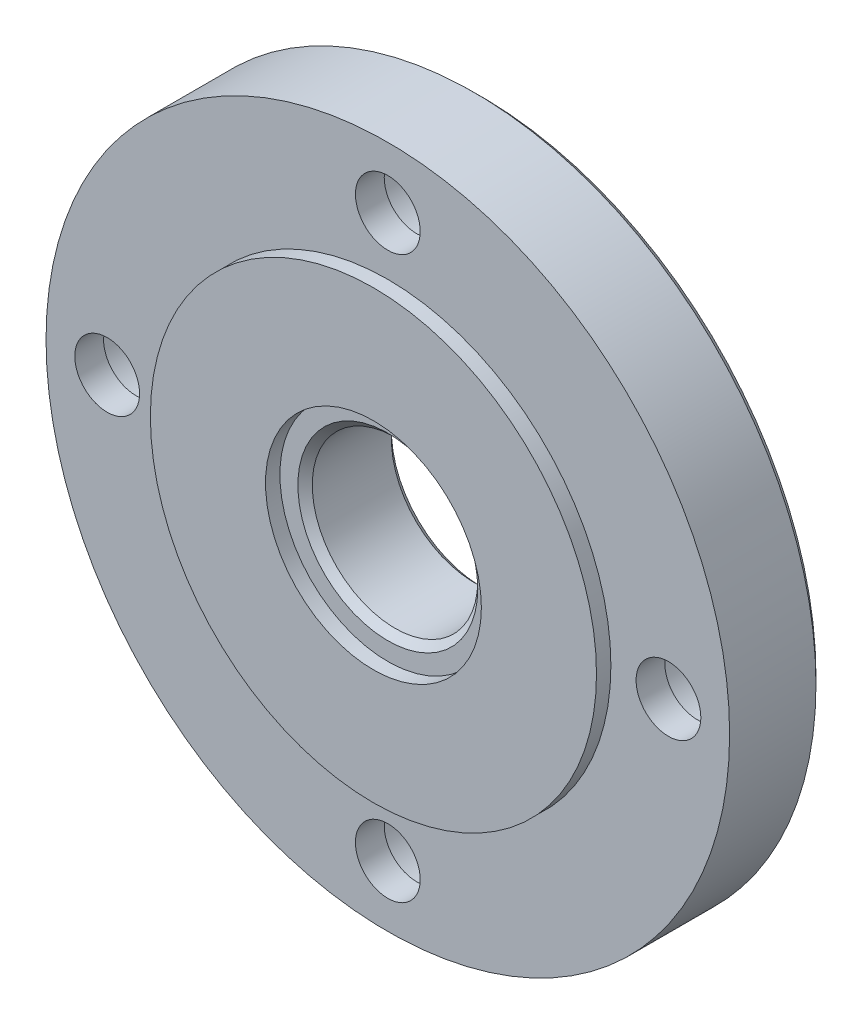
SolidWorks part; units mm, degrees
ref_plane "前视基准面" through (0, 0, 0) normal (0, 0, 1) x (1, 0, 0)
ref_plane "上视基准面" through (0, 0, 0) normal (0, 1, 0) x (1, 0, 0)
ref_plane "右视基准面" through (0, 0, 0) normal (1, 0, 0) x (0, 0, -1)
sketch "草图1" plane through (0, 0, 0) normal (0, 0, 1) x (1, 0, 0)
  circle A0 centre (0, 0) radius 47.5
  dimension "D1" = 95
extrude "凸台-拉伸1" add sketch "草图1" along normal blind 13
sketch "草图2" plane through (0, 0, 13) normal (0, 0, 1) x (1, 0, 0)
  circle A0 centre (0, 0) radius 31
  dimension "D1" = 62
extrude "凸台-拉伸2" add sketch "草图2" along normal blind 2
sketch "草图3" plane through (0, 0, 15) normal (0, 0, 1) x (1, 0, 0)
  circle A0 centre (0, 0) radius 15
  dimension "D1" = 30
extrude "切除-拉伸2" cut sketch "草图3" against normal blind 2
sketch "草图6" plane through (0, 0, 13) normal (0, 0, 1) x (1, 0, 0)
  circle A0 centre (0, 0) radius 11.5
  dimension "D1" = 23
extrude "切除-拉伸3" cut sketch "草图6" against normal through all
chamfer "倒角1" distance 1 angle 45 2 edges at (11.5, 0, 13) (11.5, 0, 0)
sketch "草图7" plane through (0, 0, 0) normal (0, 0, -1) x (-1, 0, 0)
  circle A0 centre (0, 0) radius 39 construction
  circle A1 centre (0, 39) radius 7
  dimension "D1" = 78
  dimension "D2" = 14
extrude "切除-拉伸4" cut sketch "草图7" against normal blind 9
sketch "草图8" plane through (0, 0, 9) normal (0, 0, -1) x (-1, 0, 0)
  circle A0 centre (0, 39) radius 4.5
  circle A1 centre (0, 39) radius 7 construction
  dimension "D1" = 9
extrude "切除-拉伸5" cut sketch "草图8" against normal through all
pattern_circular "阵列(圆周)1" count 4 over 360 about axis through (0, 0, 0) along (0, 0, 1) of "切除-拉伸4", "切除-拉伸5"
chamfer "倒角2" distance 1 angle 45 1 edges at (47.5, 0, 0)
